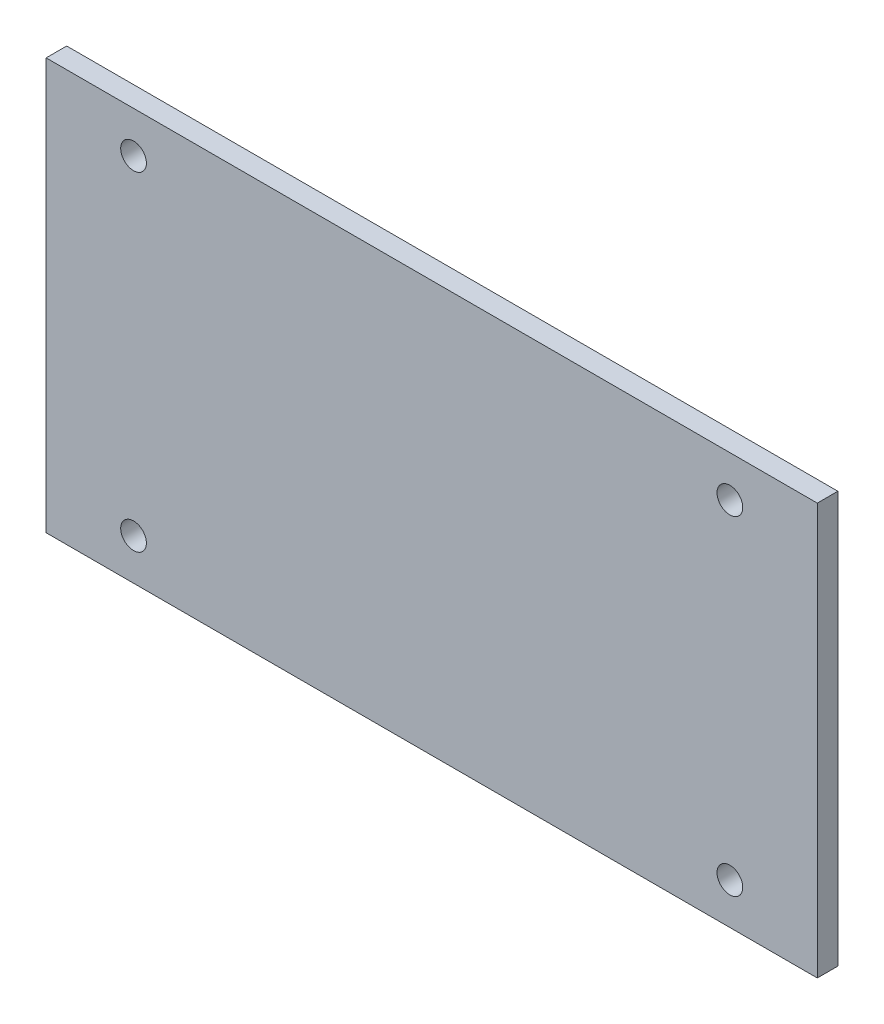
SolidWorks part; units mm, degrees
ref_plane "Plano frontal" through (0, 0, 0) normal (0, 0, 1) x (1, 0, 0)
ref_plane "Plano superior" through (0, 0, 0) normal (0, 1, 0) x (1, 0, 0)
ref_plane "Plano direito" through (0, 0, 0) normal (1, 0, 0) x (0, 0, -1)
sketch "Esboço1" plane through (0, 0, 0) normal (0, 0, 1) x (1, 0, 0)
  line L1 (-54.6557, 47.9499) -> (95.3443, 47.9499)
  line L2 (-54.6557, 47.9499) -> (-54.6557, -32.0501)
  line L3 (-54.6557, -32.0501) -> (95.3443, -32.0501)
  line L4 (95.3443, 47.9499) -> (95.3443, -32.0501)
  circle A0 centre (-37.6557, 39.9499) radius 2.5
  circle A1 centre (-37.6557, -24.0501) radius 2.5
  circle A4 centre (78.3443, 39.9499) radius 2.5
  circle A5 centre (78.3443, -24.0501) radius 2.5
  dimension "D3" = 5
  dimension "D1" = 80
  dimension "D2" = 150
  dimension "D4" = 17
  dimension "D5" = 8
  dimension "D6" = 8
  dimension "D7" = 17
extrude "Ressalto-extrusão2" add sketch "Esboço1" along normal blind 4
